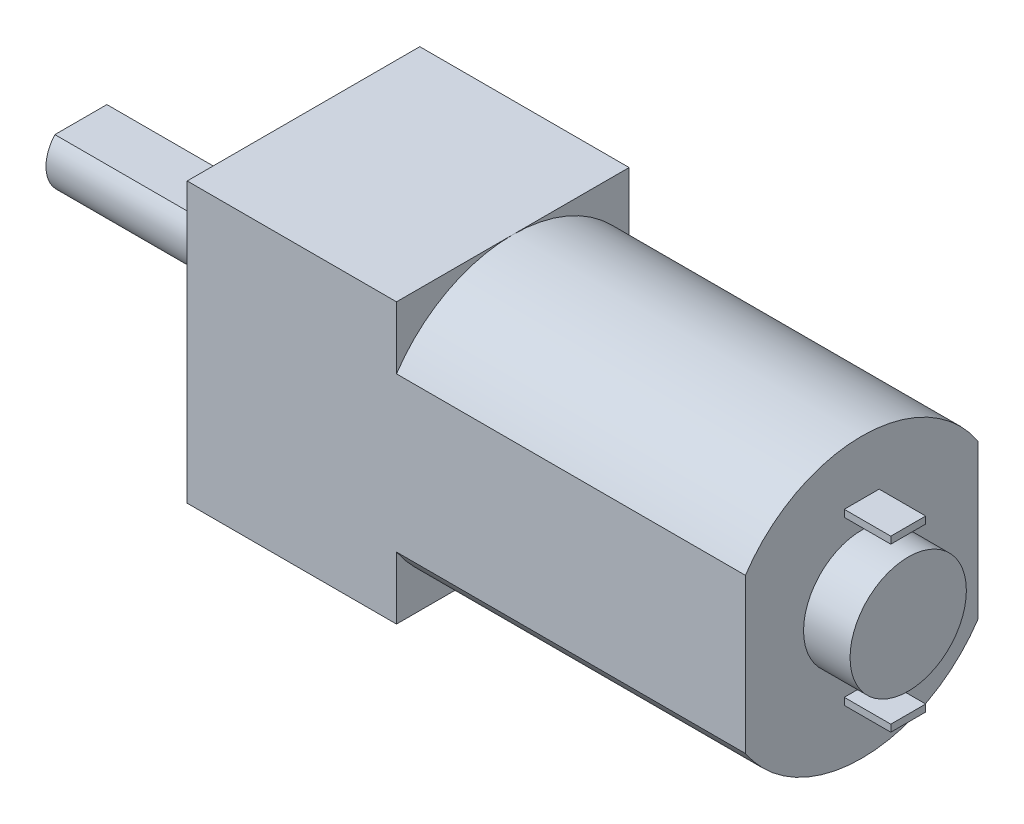
SolidWorks part; units mm, degrees
material "Plain Carbon Steel"
ref_plane "Front" through (0, 0, 0) normal (0, 0, 1) x (1, 0, 0)
ref_plane "Top" through (0, 0, 0) normal (0, 1, 0) x (1, 0, 0)
ref_plane "Right" through (0, 0, 0) normal (1, 0, 0) x (0, 0, -1)
sketch "Sketch6" plane through (0, 0, 0) normal (0, 1, 0) x (1, 0, 0)
  line L0 (0, 0) -> (15, 0)
  dimension "D1" = 15
revolve "Revolve-Thin2" add sketch "Sketch6" angle 360 about L0 wall 6
sketch "Sketch8" plane through (0, 0, 0) normal (-1, 0, 0) x (0, 0, 1)
  line L1 (-5, -6) -> (5, -6)
  line L2 (-5, -6) -> (-5, 6)
  line L3 (-5, 6) -> (5, 6)
  line L4 (5, -6) -> (5, 6)
  line L5 (-5, -6) -> (5, 6) construction
  line L6 (-5, 6) -> (5, -6) construction
  point P0 (0, 0)
  dimension "D1" = 12
  dimension "D2" = 10
extrude "Boss-Extrude2" add sketch "Sketch8" along normal blind 9
sketch "Sketch9" plane through (0, 0, 0) normal (-1, 0, 0) x (0, 0, 1)
  line L1 (5, -6) -> (6, -6)
  line L2 (5, -6) -> (5, 6)
  line L3 (5, 6) -> (6, 6)
  line L4 (6, -6) -> (6, 6)
  line L5 (-5, -6) -> (-6, -6)
  line L6 (-5, -6) -> (-5, 6)
  line L7 (-5, 6) -> (-6, 6)
  line L8 (-6, -6) -> (-6, 6)
  dimension "D1" = 12
  dimension "D2" = 1
  dimension "D3" = 1
  dimension "D4" = 12
extrude "Cut-Extrude2" cut sketch "Sketch9" against normal blind 15
sketch "Sketch10" plane through (-9, 0, 0) normal (-1, 0, 0) x (0, 0, 1)
  circle A0 centre (0, 0) radius 1.95
  dimension "D1" = 3.9
extrude "Boss-Extrude3" add sketch "Sketch10" along normal blind 0.9
sketch "Sketch11" plane through (-9.9, 0, 0) normal (-1, 0, 0) x (0, 0, 1)
  circle A0 centre (0, 0) radius 1.5
  dimension "D1" = 3
extrude "Boss-Extrude4" add sketch "Sketch11" along normal blind 8.67
sketch "Sketch12" plane through (-18.57, 0, 0) normal (-1, 0, 0) x (0, 0, 1)
  line L0 (0, 0) -> (0, 1.25) construction
  line L2 (-1.246, 1) -> (1.246, 1)
  line L3 (-1.246, 1) -> (-1.246, 1.5)
  line L4 (-1.246, 1.5) -> (1.246, 1.5)
  line L5 (1.246, 1) -> (1.246, 1.5)
  line L6 (-1.246, 1) -> (1.246, 1.5) construction
  line L7 (-1.246, 1.5) -> (1.246, 1) construction
  circle A0 centre (0, 0) radius 1.95 construction
  dimension "D1" = 1.25
  dimension "D2" = 0.5
extrude "Cut-Extrude3" cut sketch "Sketch12" against normal blind 8.67
sketch "Sketch13" plane through (15, 0, 0) normal (1, 0, 0) x (0, 0, -1)
  line L1 (-0.75, 3.65) -> (0.75, 3.65)
  line L2 (-0.75, 3.65) -> (-0.75, 3.35)
  line L3 (-0.75, 3.35) -> (0.75, 3.35)
  line L4 (0.75, 3.65) -> (0.75, 3.35)
  line L5 (-0.75, 3.65) -> (0.75, 3.35) construction
  line L6 (-0.75, 3.35) -> (0.75, 3.65) construction
  line L7 (-0.75, -3.35) -> (0.75, -3.35)
  line L8 (-0.75, -3.35) -> (-0.75, -3.65)
  line L9 (-0.75, -3.65) -> (0.75, -3.65)
  line L10 (0.75, -3.35) -> (0.75, -3.65)
  line L11 (-0.75, -3.35) -> (0.75, -3.65) construction
  line L12 (-0.75, -3.65) -> (0.75, -3.35) construction
  circle A0 centre (0, 0) radius 2.5
  point P0 (0, 3.5)
  point P5 (0, -3.5)
  dimension "D1" = 5
  dimension "D2" = 0.3
  dimension "D3" = 0.3
  dimension "D4" = 1.5
  dimension "D5" = 3.5
  dimension "D6" = 0
  dimension "D7" = 1.5
  dimension "D8" = 0
  dimension "D9" = 3.5
extrude "Boss-Extrude5" add sketch "Sketch13" along normal blind 2
